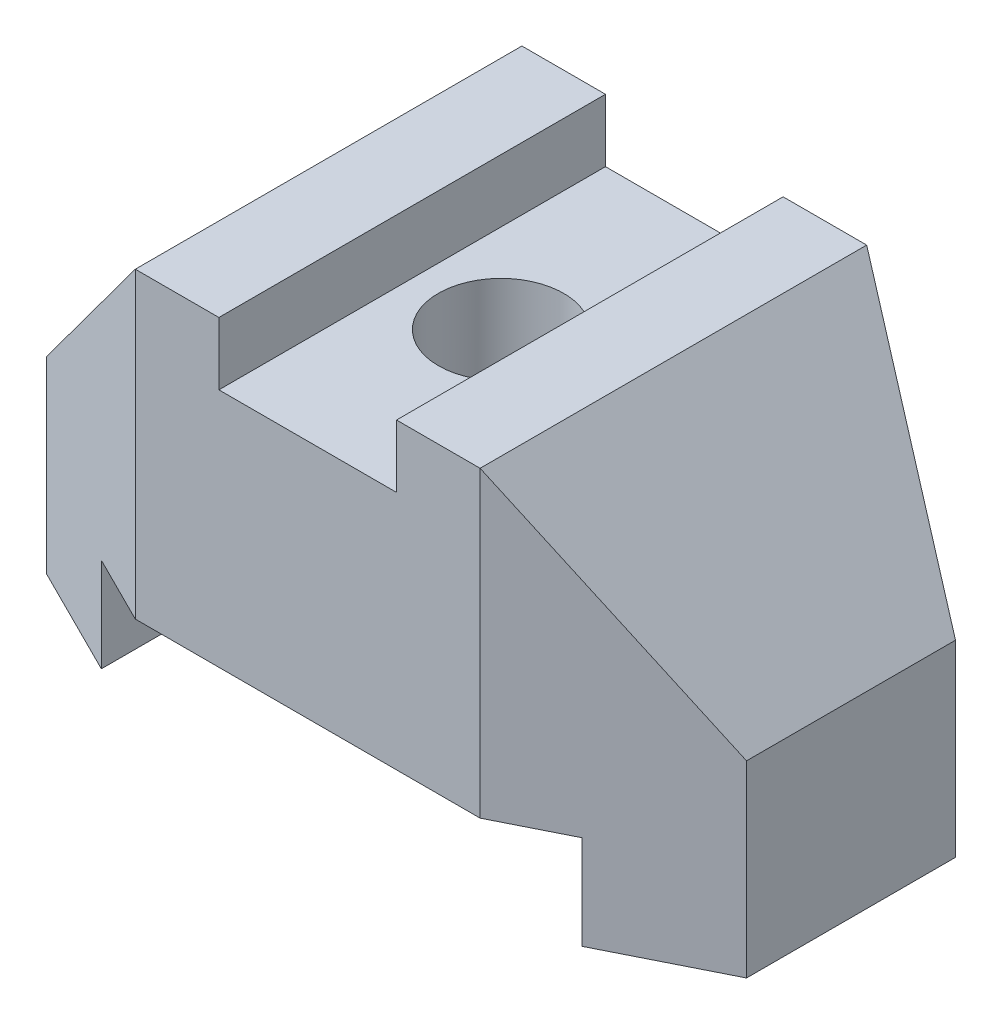
SolidWorks part; units mm, degrees
ref_plane "前视基准面" through (0, 0, 0) normal (0, 0, 1) x (1, 0, 0)
ref_plane "上视基准面" through (0, 0, 0) normal (0, 1, 0) x (1, 0, 0)
ref_plane "右视基准面" through (0, 0, 0) normal (1, 0, 0) x (0, 0, -1)
other "Configuration Table"
sketch "草图1" plane through (0, 0, 0) normal (0, 1, 0) x (1, 0, 0)
  line L0 (-54.3434, 0) -> (52.7273, 0) construction
  line L1 (0, 36.3973) -> (0, -26.5657) construction
  line L2 (-33.5, -10) -> (-33.5, 10)
  line L3 (-16.5, -18.5) -> (-16.5, 18.5)
  line L4 (-33.5, 10) -> (-16.5, 18.5)
  line L5 (-16.5, 18.5) -> (16.5, 18.5)
  line L6 (33.5, 10) -> (16.5, 18.5)
  line L7 (16.5, -18.5) -> (16.5, 18.5)
  line L8 (33.5, -10) -> (33.5, 10)
  line L9 (33.5, -10) -> (16.5, -18.5)
  line L10 (-16.5, -18.5) -> (16.5, -18.5)
  line L11 (-33.5, -10) -> (-16.5, -18.5)
  point P5 (0, -18.5)
  point P7 (-33.5, 0)
  point P11 (0, 18.5)
  point P15 (33.5, 0)
  point P16 (16.5, 0)
  point P18 (-16.5, 0)
  dimension "D1" = 20
  dimension "D2" = 37
  dimension "D3" = 33
  dimension "D4" = 67
extrude "凸台-拉伸1" add sketch "草图1" along normal blind 38 contours L2 L11 L3 L4 | L3 L10 L7 L5 | L9 L8 L6 L7
sketch "草图2" plane through (0, 0, 0) normal (0, 0, 1) x (1, 0, 0)
  line L0 (16.5, 38) -> (33.5, 18)
  line L1 (33.5, 38) -> (33.5, 0) construction
  line L2 (33.5, 0) -> (16.5, 0) construction
  dimension "D1" = 18
extrude "切除-拉伸1" cut sketch "草图2" against normal through all and the other way through all
mirror "镜向1" about plane through (0, 0, 0) normal (1, 0, 0) of "切除-拉伸1"
sketch "草图3" plane through (0, 0, 0) normal (0, 0, 1) x (1, 0, 0)
  line L0 (0, 40.8736) -> (0, -5.068) construction
  line L1 (-23, 0) -> (-23, 9)
  line L2 (-33.5, 0) -> (-16.5, 0) construction
  line L3 (-23, 9) -> (23, 9)
  line L4 (-23, 0) -> (23, 0)
  line L5 (23, 0) -> (23, 9)
  point P10 (0, 0)
  point P11 (0, 9)
  dimension "D1" = 46
  dimension "D2" = 9
extrude "切除-拉伸2" cut sketch "草图3" against normal through all both and the other way through all
sketch "草图4" plane through (0, 38, 0) normal (0, 1, 0) x (1, 0, 0)
  line L0 (0, 19.0723) -> (0, -20.5197) construction
  line L1 (-8.5, 18.5) -> (-8.5, -18.5)
  line L2 (-16.5, 18.5) -> (16.5, 18.5) construction
  line L3 (-16.5, -18.5) -> (16.5, -18.5) construction
  line L4 (-8.5, -18.5) -> (8.5, -18.5)
  line L5 (-8.5, 18.5) -> (8.5, 18.5)
  line L6 (8.5, 18.5) -> (8.5, -18.5)
  point P12 (0, 18.5)
  point P13 (0, -18.5)
  dimension "D1" = 17
extrude "切除-拉伸3" cut sketch "草图4" against normal blind 6
sketch "草图5" plane through (0, 32, 0) normal (0, 1, 0) x (1, 0, 0)
  circle A0 centre (0, 0) radius 6
  dimension "D1" = 12
extrude "切除-拉伸4" cut sketch "草图5" against normal through all
